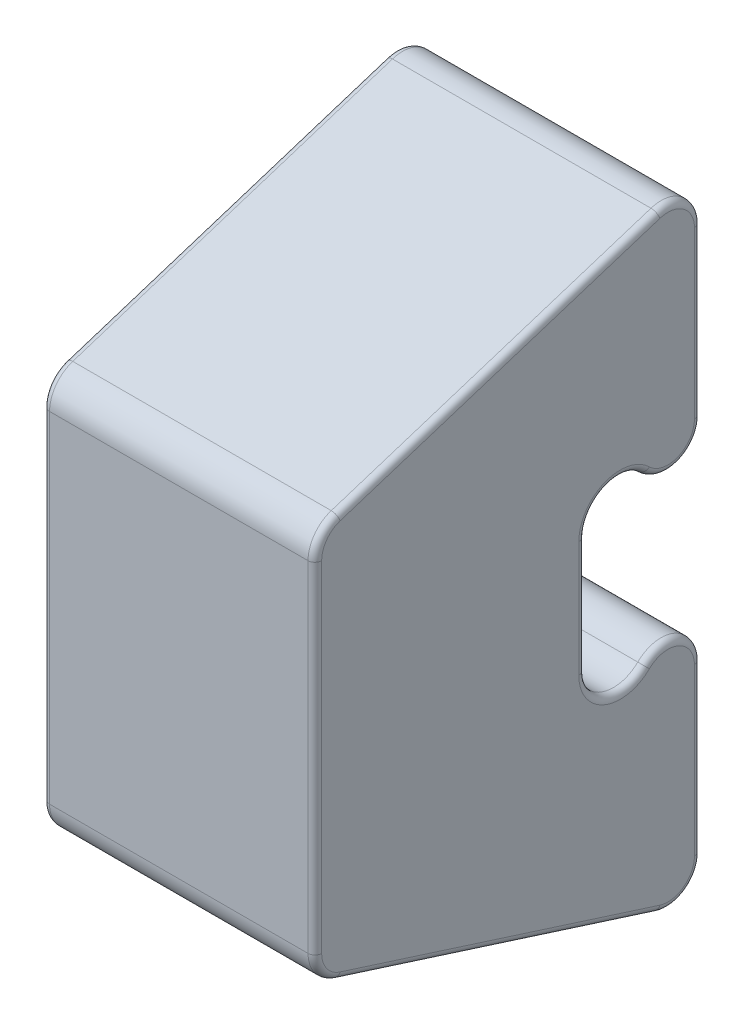
SolidWorks part; units mm, degrees
material "ABS"
ref_plane "Front Plane" through (0, 0, 0) normal (1, 0, 0) x (0, 1, 0)
ref_plane "Top Plane" through (0, 0, 0) normal (0, 0, 1) x (0, 1, 0)
ref_plane "Right Plane" through (0, 0, 0) normal (0, 1, 0) x (-1, 0, 0)
sketch "Sketch3" plane through (0, 0, 0) normal (1, 0, 0) x (0, 1, 0)
  line L12 (-4, 5.31) -> (-1.5642, 5.31)
  line L13 (-0.85, 7.01) -> (0.85, 7.01)
  line L14 (1.5642, 5.31) -> (4, 5.31)
  line L15 (4.4668, 5.949) -> (2.9668, 10.649)
  line L16 (2.5, 10.99) -> (-2.5, 10.99)
  line L17 (-2.9668, 10.649) -> (-4.4668, 5.949)
  line L18 (-4, 5.31) -> (-1.5642, 5.31)
  line L19 (-0.85, 7.01) -> (0.85, 7.01)
  line L20 (1.5642, 5.31) -> (4, 5.31)
  line L21 (4.4668, 5.949) -> (2.9668, 10.649)
  line L22 (2.5, 10.99) -> (-2.5, 10.99)
  line L23 (-2.9668, 10.649) -> (-4.4668, 5.949)
  arc A16 (-4.4668, 5.949) -> (-4, 5.31) centre (-4, 5.8) ccw
  arc A17 (-1.5642, 5.31) -> (-1.2142, 6.143) centre (-1.5642, 5.8) ccw
  arc A18 (-0.85, 7.01) -> (-1.2142, 6.143) centre (-0.85, 6.5) ccw
  arc A19 (1.2142, 6.143) -> (0.85, 7.01) centre (0.85, 6.5) ccw
  arc A20 (1.2142, 6.143) -> (1.5642, 5.31) centre (1.5642, 5.8) ccw
  arc A21 (4, 5.31) -> (4.4668, 5.949) centre (4, 5.8) ccw
  arc A22 (2.9668, 10.649) -> (2.5, 10.99) centre (2.5, 10.5) ccw
  arc A23 (-2.5, 10.99) -> (-2.9668, 10.649) centre (-2.5, 10.5) ccw
  arc A24 (-4.4668, 5.949) -> (-4, 5.31) centre (-4, 5.8) ccw
  arc A25 (-1.5642, 5.31) -> (-1.2142, 6.143) centre (-1.5642, 5.8) ccw
  arc A26 (-0.85, 7.01) -> (-1.2142, 6.143) centre (-0.85, 6.5) ccw
  arc A27 (1.2142, 6.143) -> (0.85, 7.01) centre (0.85, 6.5) ccw
  arc A28 (1.2142, 6.143) -> (1.5642, 5.31) centre (1.5642, 5.8) ccw
  arc A29 (4, 5.31) -> (4.4668, 5.949) centre (4, 5.8) ccw
  arc A30 (2.9668, 10.649) -> (2.5, 10.99) centre (2.5, 10.5) ccw
  arc A31 (-2.5, 10.99) -> (-2.9668, 10.649) centre (-2.5, 10.5) ccw
  dimension "D1" = 0.01
extrude "Boss-Extrude1" add sketch "Sketch3" along normal blind 1 and the other way blind 3
fillet "Fillet1" radius 0.1 28 edges at (-3, -2.7821, 5.31) (-3, -1.1124, 5.6102) (-3, -1.3202, 6.6975) (-3, 0, 7.01) (-3, 1.3202, 6.6975) (-3, 1.1124, 5.6102) (-3, 2.7821, 5.31) (-3, 4.3957, 5.5109) (-3, 3.7168, 8.299) (-3, 2.7891, 10.8957) (-3, 0, 10.99) (-3, -2.7891, 10.8957) (-3, -3.7168, 8.299) (-3, -4.3957, 5.5109) (1, -3.7168, 8.299) (1, -2.7891, 10.8957) (1, 0, 10.99) (1, 2.7891, 10.8957) (1, 3.7168, 8.299) (1, 4.3957, 5.5109) (1, 2.7821, 5.31) (1, 1.1124, 5.6102) (1, 1.3202, 6.6975) (1, 0, 7.01) (1, -1.3202, 6.6975) (1, -1.1124, 5.6102) (1, -2.7821, 5.31) (1, -4.3957, 5.5109)
